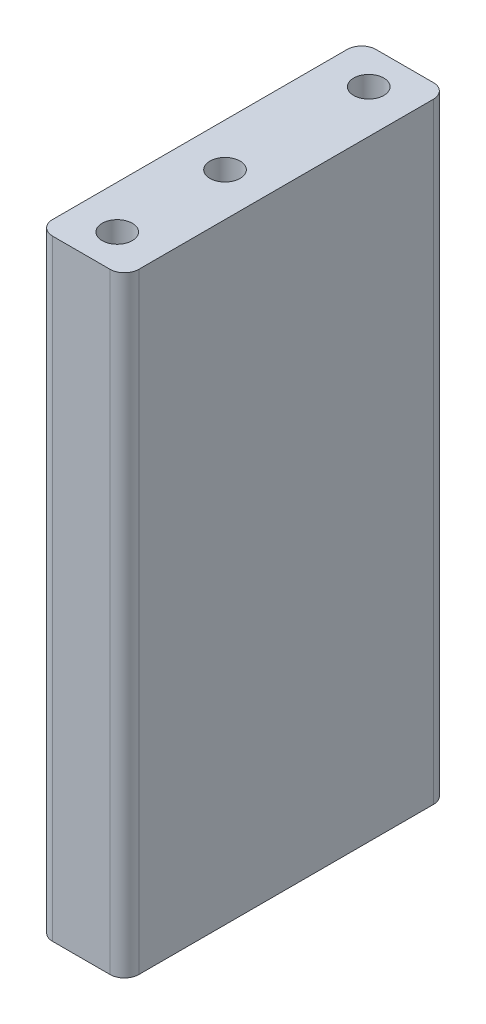
SolidWorks part; units mm, degrees
material "ABS"
ref_plane "Front Plane" through (0, 0, 0) normal (0, 0, 1) x (1, 0, 0)
ref_plane "Top Plane" through (0, 0, 0) normal (0, 1, 0) x (1, 0, 0)
ref_plane "Right Plane" through (0, 0, 0) normal (1, 0, 0) x (0, 0, -1)
sketch "Sketch1" plane through (0, 0, 0) normal (0, 1, 0) x (1, 0, 0)
  line L0 (0, 10) -> (0, -10) construction
  line L1 (-6, 30) -> (6, 30)
  line L2 (-6, 30) -> (-6, -30)
  line L3 (-6, -30) -> (6, -30)
  line L4 (6, 30) -> (6, -30)
  line L5 (0, 25) -> (0, -25) construction
  line L6 (6, 15) -> (-6, 15)
  circle A0 centre (0, 10) radius 2.5 construction
  circle A1 centre (0, -10) radius 2.5 construction
  circle A2 centre (0, 25) radius 2.5 construction
  circle A3 centre (0, -25) radius 2.5 construction
  point P8 (0, 30)
  point P9 (0, 0)
  point P10 (-6, 0)
  point P16 (0, 0)
  dimension "D2" = 5
  dimension "D1" = 20
  dimension "D3" = 12
  dimension "D4" = 60
  dimension "D5" = 50
  dimension "D6" = 5
extrude "Boss-Extrude1" add sketch "Sketch1" against normal blind 85 contours L4 L6 L2 L3
hole_wizard "Tap Drill for M5x0.8 Tap1" positions "3DSketch1" profile "Sketch2" hole size "M5x0.8" standard "ANSI Metric" end condition up to next
sketch3d "3DSketch1"
  point P19 (0, 0, -10)
  point P21 (0, 0, 10)
  point P23 (0, 0, 25)
sketch "Sketch2" plane through (0, 0, -10) normal (1, 0, 0) x (0, 0, 1)
  line L0 (0, 0) -> (0, 85)
  line L1 (0, 85) -> (2.1, 85)
  line L2 (2.1, 85) -> (2.1, 0)
  line L5 (2.1, 0) -> (0, 0)
  line L11 (0, -6.35) -> (0, 107.95) construction
  dimension "Thru Hole Dia." = 4.2
  dimension "Thru Hole Depth" = 85
fillet "Fillet1" radius 2 4 edges at (-6, -42.5, 30) (6, -42.5, 30) (-6, -42.5, -15) (6, -42.5, -15)
